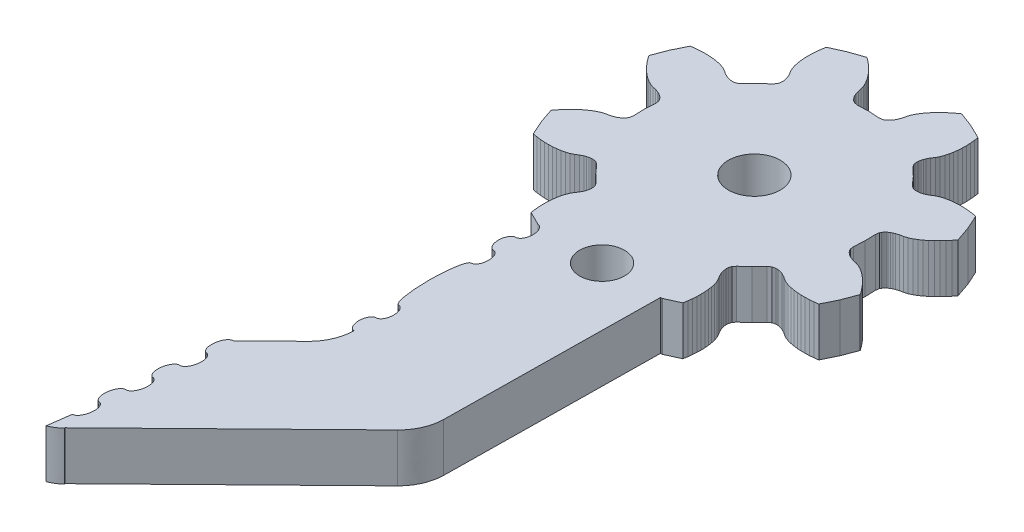
SolidWorks part; units mm, degrees
material "Acrylic (Medium-high impact)"
ref_plane "Front Plane" through (0, 0, 0) normal (0, 0, 1) x (1, 0, 0)
ref_plane "Top Plane" through (0, 0, 0) normal (0, 1, 0) x (1, 0, 0)
ref_plane "Right Plane" through (0, 0, 0) normal (1, 0, 0) x (0, 0, -1)
sketch "Sketch1" plane through (0, 0, 0) normal (0, 1, 0) x (1, 0, 0)
  line L0 (-12.9722, -46.204) -> (-9.9774, -46.2042) construction
  line L1 (-12.7972, -56.1695) -> (-10.1524, -56.2027) construction
  line L104 (-7.6081, -56.2225) -> (-7.5114, -56.2225)
  line L105 (-7.5114, -56.2225) -> (-6.5716, -55.7965)
  line L106 (-6.5716, -55.7965) -> (-6.5251, -55.515)
  line L107 (-6.5251, -55.515) -> (-6.4922, -55.2377)
  line L108 (-6.4922, -55.2377) -> (-6.4726, -54.9654)
  line L109 (-6.4726, -54.9654) -> (-6.467, -54.6985)
  line L110 (-6.467, -54.6985) -> (-6.4753, -54.4376)
  line L111 (-6.4753, -54.4376) -> (-6.4979, -54.184)
  line L112 (-6.4979, -54.184) -> (-6.5358, -53.938)
  line L113 (-6.5358, -53.938) -> (-6.5896, -53.7015)
  line L114 (-6.5896, -53.7015) -> (-6.6624, -53.4766)
  line L115 (-6.6624, -53.4766) -> (-6.7641, -53.2707)
  line L116 (-6.7641, -53.2707) -> (-6.8871, -53.0787)
  line L117 (-6.8871, -53.0787) -> (-6.988, -52.8719)
  line L118 (-6.988, -52.8719) -> (-7.028, -52.7616)
  line L119 (-7.028, -52.7616) -> (-7.0596, -52.6449)
  line L120 (-7.0596, -52.6449) -> (-7.0798, -52.5206)
  line L121 (-7.0798, -52.5206) -> (-7.0845, -52.4542)
  line L122 (-7.0845, -52.4542) -> (-7.0844, -52.3844)
  line L123 (-7.0844, -52.3844) -> (-7.0777, -52.3094)
  line L124 (-7.0777, -52.3094) -> (-7.061, -52.2267)
  line L125 (-7.061, -52.2267) -> (-7.026, -52.1298)
  line L126 (-7.026, -52.1298) -> (-6.8869, -51.9499)
  line L127 (-6.8869, -51.9499) -> (-6.3581, -51.4836)
  line L128 (-6.3581, -51.4836) -> (-5.8762, -50.9687)
  line L129 (-5.8762, -50.9687) -> (-5.6922, -50.835)
  line L130 (-5.6922, -50.835) -> (-5.5944, -50.8032)
  line L131 (-5.5944, -50.8032) -> (-5.5115, -50.7891)
  line L132 (-5.5115, -50.7891) -> (-5.4365, -50.7845)
  line L133 (-5.4365, -50.7845) -> (-5.3668, -50.7865)
  line L134 (-5.3668, -50.7865) -> (-5.3007, -50.7934)
  line L135 (-5.3007, -50.7934) -> (-5.1772, -50.8176)
  line L136 (-5.1772, -50.8176) -> (-5.062, -50.8528)
  line L137 (-5.062, -50.8528) -> (-4.953, -50.8965)
  line L138 (-4.953, -50.8965) -> (-4.7499, -51.0039)
  line L139 (-4.7499, -51.0039) -> (-4.5622, -51.1329)
  line L140 (-4.5622, -51.1329) -> (-4.36, -51.2414)
  line L141 (-4.36, -51.2414) -> (-4.1378, -51.3212)
  line L142 (-4.1378, -51.3212) -> (-3.9037, -51.3827)
  line L143 (-3.9037, -51.3827) -> (-3.6595, -51.4282)
  line L144 (-3.6595, -51.4282) -> (-3.4069, -51.4589)
  line L145 (-3.4069, -51.4589) -> (-3.1472, -51.4754)
  line L146 (-3.1472, -51.4754) -> (-2.8806, -51.4781)
  line L147 (-2.8806, -51.4781) -> (-2.6083, -51.4673)
  line L148 (-2.6083, -51.4673) -> (-2.3306, -51.4429)
  line L149 (-2.3306, -51.4429) -> (-2.0483, -51.4052)
  line L150 (-2.0483, -51.4052) -> (-1.5937, -50.4776)
  line L151 (-1.5937, -50.4776) -> (-1.2299, -49.5105)
  line L152 (-1.2299, -49.5105) -> (-1.3956, -49.2785)
  line L153 (-1.3956, -49.2785) -> (-1.568, -49.0592)
  line L154 (-1.568, -49.0592) -> (-1.7466, -48.8529)
  line L155 (-1.7466, -48.8529) -> (-1.9309, -48.66)
  line L156 (-1.9309, -48.66) -> (-2.1209, -48.4815)
  line L157 (-2.1209, -48.4815) -> (-2.3161, -48.3182)
  line L158 (-2.3161, -48.3182) -> (-2.5163, -48.171)
  line L159 (-2.5163, -48.171) -> (-2.7213, -48.0421)
  line L160 (-2.7213, -48.0421) -> (-2.9315, -47.9345)
  line L161 (-2.9315, -47.9345) -> (-3.1488, -47.861)
  line L162 (-3.1488, -47.861) -> (-3.3712, -47.8122)
  line L163 (-3.3712, -47.8122) -> (-3.5886, -47.7374)
  line L164 (-3.5886, -47.7374) -> (-3.6949, -47.6879)
  line L165 (-3.6949, -47.6879) -> (-3.7993, -47.6278)
  line L166 (-3.7993, -47.6278) -> (-3.9017, -47.5542)
  line L167 (-3.9017, -47.5542) -> (-3.9516, -47.5106)
  line L168 (-3.9516, -47.5106) -> (-4.0009, -47.4611)
  line L169 (-4.0009, -47.4611) -> (-4.0491, -47.403)
  line L170 (-4.0491, -47.403) -> (-4.0955, -47.3328)
  line L171 (-4.0955, -47.3328) -> (-4.1393, -47.2398)
  line L172 (-4.1393, -47.2398) -> (-4.1679, -47.0139)
  line L173 (-4.1679, -47.0139) -> (-4.1232, -46.3095)
  line L174 (-4.1232, -46.3095) -> (-4.1458, -45.6041)
  line L175 (-4.1458, -45.6041) -> (-4.1101, -45.3792)
  line L176 (-4.1101, -45.3792) -> (-4.0634, -45.2876)
  line L177 (-4.0634, -45.2876) -> (-4.0147, -45.2188)
  line L178 (-4.0147, -45.2188) -> (-3.9649, -45.1626)
  line L179 (-3.9649, -45.1626) -> (-3.9141, -45.1145)
  line L180 (-3.9141, -45.1145) -> (-3.8627, -45.0724)
  line L181 (-3.8627, -45.0724) -> (-3.7582, -45.0022)
  line L182 (-3.7582, -45.0022) -> (-3.6519, -44.9454)
  line L183 (-3.6519, -44.9454) -> (-3.544, -44.8991)
  line L184 (-3.544, -44.8991) -> (-3.3245, -44.8313)
  line L185 (-3.3245, -44.8313) -> (-3.1006, -44.7896)
  line L186 (-3.1006, -44.7896) -> (-2.8812, -44.723)
  line L187 (-2.8812, -44.723) -> (-2.6677, -44.6221)
  line L188 (-2.6677, -44.6221) -> (-2.4586, -44.4996)
  line L189 (-2.4586, -44.4996) -> (-2.254, -44.3588)
  line L190 (-2.254, -44.3588) -> (-2.0537, -44.2015)
  line L191 (-2.0537, -44.2015) -> (-1.8585, -44.0292)
  line L192 (-1.8585, -44.0292) -> (-1.6681, -43.8423)
  line L193 (-1.6681, -43.8423) -> (-1.4831, -43.6416)
  line L194 (-1.4831, -43.6416) -> (-1.304, -43.4279)
  line L195 (-1.304, -43.4279) -> (-1.131, -43.2013)
  line L196 (-1.131, -43.2013) -> (-1.4644, -42.2232)
  line L197 (-1.4644, -42.2232) -> (-1.8896, -41.2816)
  line L198 (-1.8896, -41.2816) -> (-2.1705, -41.2351)
  line L199 (-2.1705, -41.2351) -> (-2.4473, -41.202)
  line L200 (-2.4473, -41.202) -> (-2.7192, -41.1825)
  line L201 (-2.7192, -41.1825) -> (-2.9856, -41.1769)
  line L202 (-2.9856, -41.1769) -> (-3.2459, -41.1853)
  line L203 (-3.2459, -41.1853) -> (-3.4992, -41.2079)
  line L204 (-3.4992, -41.2079) -> (-3.7446, -41.2457)
  line L205 (-3.7446, -41.2457) -> (-3.9807, -41.2997)
  line L206 (-3.9807, -41.2997) -> (-4.2052, -41.3725)
  line L207 (-4.2052, -41.3725) -> (-4.4107, -41.4746)
  line L208 (-4.4107, -41.4746) -> (-4.6025, -41.5978)
  line L209 (-4.6025, -41.5978) -> (-4.809, -41.6987)
  line L210 (-4.809, -41.6987) -> (-4.9191, -41.739)
  line L211 (-4.9191, -41.739) -> (-5.0354, -41.7705)
  line L212 (-5.0354, -41.7705) -> (-5.1596, -41.7909)
  line L213 (-5.1596, -41.7909) -> (-5.2257, -41.7956)
  line L214 (-5.2257, -41.7956) -> (-5.2956, -41.7954)
  line L215 (-5.2956, -41.7954) -> (-5.3704, -41.7885)
  line L216 (-5.3704, -41.7885) -> (-5.4528, -41.7718)
  line L217 (-5.4528, -41.7718) -> (-5.5495, -41.737)
  line L218 (-5.5495, -41.737) -> (-5.7293, -41.5975)
  line L219 (-5.7293, -41.5975) -> (-6.1948, -41.0677)
  line L220 (-6.1948, -41.0677) -> (-6.7088, -40.5851)
  line L221 (-6.7088, -40.5851) -> (-6.842, -40.4008)
  line L222 (-6.842, -40.4008) -> (-6.8739, -40.3028)
  line L223 (-6.8739, -40.3028) -> (-6.888, -40.2197)
  line L224 (-6.888, -40.2197) -> (-6.8924, -40.1446)
  line L225 (-6.8924, -40.1446) -> (-6.8906, -40.0745)
  line L226 (-6.8906, -40.0745) -> (-6.8837, -40.0085)
  line L227 (-6.8837, -40.0085) -> (-6.8594, -39.8848)
  line L228 (-6.8594, -39.8848) -> (-6.8243, -39.7694)
  line L229 (-6.8243, -39.7694) -> (-6.7808, -39.6602)
  line L230 (-6.7808, -39.6602) -> (-6.6734, -39.4568)
  line L231 (-6.6734, -39.4568) -> (-6.5447, -39.2687)
  line L232 (-6.5447, -39.2687) -> (-6.4364, -39.066)
  line L233 (-6.4364, -39.066) -> (-6.3567, -38.8435)
  line L234 (-6.3567, -38.8435) -> (-6.2953, -38.6088)
  line L235 (-6.2953, -38.6088) -> (-6.25, -38.3642)
  line L236 (-6.25, -38.3642) -> (-6.2192, -38.1113)
  line L237 (-6.2192, -38.1113) -> (-6.2028, -37.851)
  line L238 (-6.2028, -37.851) -> (-6.2002, -37.5841)
  line L239 (-6.2002, -37.5841) -> (-6.2111, -37.3112)
  line L240 (-6.2111, -37.3112) -> (-6.2353, -37.0331)
  line L241 (-6.2353, -37.0331) -> (-6.2729, -36.7502)
  line L242 (-6.2729, -36.7502) -> (-7.199, -36.2948)
  line L243 (-7.199, -36.2948) -> (-8.1643, -35.9303)
  line L244 (-8.1643, -35.9303) -> (-8.3957, -36.0963)
  line L245 (-8.3957, -36.0963) -> (-8.6147, -36.269)
  line L246 (-8.6147, -36.269) -> (-8.8207, -36.4479)
  line L247 (-8.8207, -36.4479) -> (-9.0131, -36.6326)
  line L248 (-9.0131, -36.6326) -> (-9.1913, -36.823)
  line L249 (-9.1913, -36.823) -> (-9.3545, -37.0183)
  line L250 (-9.3545, -37.0183) -> (-9.5013, -37.2189)
  line L251 (-9.5013, -37.2189) -> (-9.6301, -37.4244)
  line L252 (-9.6301, -37.4244) -> (-9.7373, -37.6349)
  line L253 (-9.7373, -37.6349) -> (-9.8108, -37.8528)
  line L254 (-9.8108, -37.8528) -> (-9.8594, -38.0756)
  line L255 (-9.8594, -38.0756) -> (-9.934, -38.2931)
  line L256 (-9.934, -38.2931) -> (-9.9834, -38.3996)
  line L257 (-9.9834, -38.3996) -> (-10.0435, -38.5044)
  line L258 (-10.0435, -38.5044) -> (-10.1169, -38.6068)
  line L259 (-10.1169, -38.6068) -> (-10.1605, -38.657)
  line L260 (-10.1605, -38.657) -> (-10.21, -38.7062)
  line L261 (-10.21, -38.7062) -> (-10.2677, -38.7545)
  line L262 (-10.2677, -38.7545) -> (-10.3378, -38.8011)
  line L263 (-10.3378, -38.8011) -> (-10.4309, -38.8448)
  line L264 (-10.4309, -38.8448) -> (-10.6564, -38.8737)
  line L265 (-10.6564, -38.8737) -> (-11.3595, -38.8287)
  line L266 (-11.3595, -38.8287) -> (-12.0636, -38.8515)
  line L267 (-12.0636, -38.8515) -> (-12.288, -38.8156)
  line L268 (-12.288, -38.8156) -> (-12.3796, -38.769)
  line L269 (-12.3796, -38.769) -> (-12.4482, -38.7201)
  line L270 (-12.4482, -38.7201) -> (-12.5044, -38.6701)
  line L271 (-12.5044, -38.6701) -> (-12.5523, -38.6193)
  line L272 (-12.5523, -38.6193) -> (-12.5942, -38.5678)
  line L273 (-12.5942, -38.5678) -> (-12.6645, -38.4631)
  line L274 (-12.6645, -38.4631) -> (-12.7211, -38.3566)
  line L275 (-12.7211, -38.3566) -> (-12.7673, -38.2486)
  line L276 (-12.7673, -38.2486) -> (-12.835, -38.0288)
  line L277 (-12.835, -38.0288) -> (-12.8765, -37.8045)
  line L278 (-12.8765, -37.8045) -> (-12.9431, -37.5846)
  line L279 (-12.9431, -37.5846) -> (-13.0439, -37.3707)
  line L280 (-13.0439, -37.3707) -> (-13.1661, -37.1613)
  line L281 (-13.1661, -37.1613) -> (-13.3065, -36.9563)
  line L282 (-13.3065, -36.9563) -> (-13.4634, -36.7557)
  line L283 (-13.4634, -36.7557) -> (-13.6357, -36.5599)
  line L284 (-13.6357, -36.5599) -> (-13.8221, -36.3692)
  line L285 (-13.8221, -36.3692) -> (-14.0224, -36.184)
  line L286 (-14.0224, -36.184) -> (-14.2359, -36.0044)
  line L287 (-14.2359, -36.0044) -> (-14.4621, -35.8312)
  line L288 (-14.4621, -35.8312) -> (-15.4384, -36.1651)
  line L289 (-15.4384, -36.1651) -> (-16.3783, -36.5911)
  line L290 (-16.3783, -36.5911) -> (-16.4247, -36.8727)
  line L291 (-16.4247, -36.8727) -> (-16.4578, -37.1499)
  line L292 (-16.4578, -37.1499) -> (-16.477, -37.4222)
  line L293 (-16.477, -37.4222) -> (-16.4826, -37.6893)
  line L294 (-16.4826, -37.6893) -> (-16.4745, -37.95)
  line L295 (-16.4745, -37.95) -> (-16.4517, -38.2038)
  line L296 (-16.4517, -38.2038) -> (-16.4141, -38.4497)
  line L297 (-16.4141, -38.4497) -> (-16.36, -38.6861)
  line L298 (-16.36, -38.6861) -> (-16.2874, -38.911)
  line L299 (-16.2874, -38.911) -> (-16.1854, -39.117)
  line L300 (-16.1854, -39.117) -> (-16.0626, -39.3089)
  line L301 (-16.0626, -39.3089) -> (-15.9617, -39.5157)
  line L302 (-15.9617, -39.5157) -> (-15.9218, -39.6261)
  line L303 (-15.9218, -39.6261) -> (-15.8901, -39.7427)
  line L304 (-15.8901, -39.7427) -> (-15.8699, -39.8672)
  line L305 (-15.8699, -39.8672) -> (-15.8652, -39.9334)
  line L306 (-15.8652, -39.9334) -> (-15.8654, -40.0032)
  line L307 (-15.8654, -40.0032) -> (-15.8721, -40.0784)
  line L308 (-15.8721, -40.0784) -> (-15.8888, -40.1609)
  line L309 (-15.8888, -40.1609) -> (-15.9237, -40.2578)
  line L310 (-15.9237, -40.2578) -> (-16.0628, -40.4378)
  line L311 (-16.0628, -40.4378) -> (-16.5916, -40.9042)
  line L312 (-16.5916, -40.9042) -> (-17.0735, -41.419)
  line L313 (-17.0735, -41.419) -> (-17.2575, -41.5527)
  line L314 (-17.2575, -41.5527) -> (-17.3552, -41.5844)
  line L315 (-17.3552, -41.5844) -> (-17.4381, -41.5985)
  line L316 (-17.4381, -41.5985) -> (-17.5133, -41.6031)
  line L317 (-17.5133, -41.6031) -> (-17.583, -41.6011)
  line L318 (-17.583, -41.6011) -> (-17.6491, -41.5944)
  line L319 (-17.6491, -41.5944) -> (-17.7726, -41.5701)
  line L320 (-17.7726, -41.5701) -> (-17.8878, -41.5349)
  line L321 (-17.8878, -41.5349) -> (-17.9966, -41.4911)
  line L322 (-17.9966, -41.4911) -> (-18.1998, -41.3838)
  line L323 (-18.1998, -41.3838) -> (-18.3875, -41.2547)
  line L324 (-18.3875, -41.2547) -> (-18.5899, -41.1462)
  line L325 (-18.5899, -41.1462) -> (-18.812, -41.0664)
  line L326 (-18.812, -41.0664) -> (-19.0461, -41.0049)
  line L327 (-19.0461, -41.0049) -> (-19.2902, -40.9594)
  line L328 (-19.2902, -40.9594) -> (-19.5427, -40.9287)
  line L329 (-19.5427, -40.9287) -> (-19.8027, -40.9122)
  line L330 (-19.8027, -40.9122) -> (-20.0692, -40.9095)
  line L331 (-20.0692, -40.9095) -> (-20.3415, -40.9204)
  line L332 (-20.3415, -40.9204) -> (-20.6192, -40.9447)
  line L333 (-20.6192, -40.9447) -> (-20.9015, -40.9824)
  line L334 (-20.9015, -40.9824) -> (-21.3561, -41.9101)
  line L335 (-21.3561, -41.9101) -> (-21.7199, -42.8771)
  line L336 (-21.7199, -42.8771) -> (-21.554, -43.1091)
  line L337 (-21.554, -43.1091) -> (-21.3818, -43.3285)
  line L338 (-21.3818, -43.3285) -> (-21.2032, -43.5347)
  line L339 (-21.2032, -43.5347) -> (-21.0187, -43.7277)
  line L340 (-21.0187, -43.7277) -> (-20.8289, -43.9062)
  line L341 (-20.8289, -43.9062) -> (-20.6337, -44.0696)
  line L342 (-20.6337, -44.0696) -> (-20.4335, -44.2168)
  line L343 (-20.4335, -44.2168) -> (-20.2284, -44.3456)
  line L344 (-20.2284, -44.3456) -> (-20.0183, -44.4531)
  line L345 (-20.0183, -44.4531) -> (-19.801, -44.5266)
  line L346 (-19.801, -44.5266) -> (-19.5786, -44.5755)
  line L347 (-19.5786, -44.5755) -> (-19.3612, -44.6502)
  line L348 (-19.3612, -44.6502) -> (-19.255, -44.6998)
  line L349 (-19.255, -44.6998) -> (-19.1504, -44.76)
  line L350 (-19.1504, -44.76) -> (-19.0481, -44.8335)
  line L351 (-19.0481, -44.8335) -> (-18.9981, -44.877)
  line L352 (-18.9981, -44.877) -> (-18.9489, -44.9267)
  line L353 (-18.9489, -44.9267) -> (-18.9009, -44.9846)
  line L354 (-18.9009, -44.9846) -> (-18.8543, -45.0548)
  line L355 (-18.8543, -45.0548) -> (-18.8105, -45.1479)
  line L356 (-18.8105, -45.1479) -> (-18.7817, -45.3737)
  line L357 (-18.7817, -45.3737) -> (-18.8266, -46.0782)
  line L358 (-18.8266, -46.0782) -> (-18.804, -46.7836)
  line L359 (-18.804, -46.7836) -> (-18.8397, -47.0085)
  line L360 (-18.8397, -47.0085) -> (-18.8864, -47.1002)
  line L361 (-18.8864, -47.1002) -> (-18.9351, -47.1688)
  line L362 (-18.9351, -47.1688) -> (-18.9849, -47.2252)
  line L363 (-18.9849, -47.2252) -> (-19.0356, -47.2731)
  line L364 (-19.0356, -47.2731) -> (-19.0871, -47.3152)
  line L365 (-19.0871, -47.3152) -> (-19.1915, -47.3855)
  line L366 (-19.1915, -47.3855) -> (-19.2978, -47.4422)
  line L367 (-19.2978, -47.4422) -> (-19.4058, -47.4885)
  line L368 (-19.4058, -47.4885) -> (-19.6252, -47.5565)
  line L369 (-19.6252, -47.5565) -> (-19.8489, -47.5981)
  line L370 (-19.8489, -47.5981) -> (-20.0686, -47.6648)
  line L371 (-20.0686, -47.6648) -> (-20.282, -47.7656)
  line L372 (-20.282, -47.7656) -> (-20.4911, -47.8882)
  line L373 (-20.4911, -47.8882) -> (-20.6958, -48.0288)
  line L374 (-20.6958, -48.0288) -> (-20.8959, -48.1861)
  line L375 (-20.8959, -48.1861) -> (-21.0915, -48.3584)
  line L376 (-21.0915, -48.3584) -> (-21.2818, -48.5453)
  line L377 (-21.2818, -48.5453) -> (-21.4667, -48.746)
  line L378 (-21.4667, -48.746) -> (-21.6459, -48.9599)
  line L379 (-21.6459, -48.9599) -> (-21.8188, -49.1865)
  line L380 (-21.8188, -49.1865) -> (-21.4856, -50.1646)
  line L381 (-21.4856, -50.1646) -> (-21.0601, -51.106)
  line L382 (-21.0601, -51.106) -> (-20.7793, -51.1527)
  line L383 (-20.7793, -51.1527) -> (-20.5024, -51.1856)
  line L384 (-20.5024, -51.1856) -> (-20.2305, -51.2051)
  line L385 (-20.2305, -51.2051) -> (-19.9641, -51.2107)
  line L386 (-19.9641, -51.2107) -> (-19.7039, -51.2024)
  line L387 (-19.7039, -51.2024) -> (-19.4505, -51.1797)
  line L388 (-19.4505, -51.1797) -> (-19.2051, -51.1419)
  line L389 (-19.2051, -51.1419) -> (-18.9691, -51.0879)
  line L390 (-18.9691, -51.0879) -> (-18.7446, -51.0151)
  line L391 (-18.7446, -51.0151) -> (-18.5388, -50.913)
  line L392 (-18.5388, -50.913) -> (-18.3474, -50.79)
  line L393 (-18.3474, -50.79) -> (-18.141, -50.6889)
  line L394 (-18.141, -50.6889) -> (-18.0307, -50.6486)
  line L395 (-18.0307, -50.6486) -> (-17.9144, -50.6171)
  line L396 (-17.9144, -50.6171) -> (-17.7902, -50.5967)
  line L397 (-17.7902, -50.5967) -> (-17.7239, -50.592)
  line L398 (-17.7239, -50.592) -> (-17.6542, -50.5924)
  line L399 (-17.6542, -50.5924) -> (-17.5794, -50.5991)
  line L400 (-17.5794, -50.5991) -> (-17.4968, -50.6158)
  line L401 (-17.4968, -50.6158) -> (-17.4003, -50.6506)
  line L402 (-17.4003, -50.6506) -> (-17.2204, -50.7902)
  line L403 (-17.2204, -50.7902) -> (-16.755, -51.3199)
  line L404 (-16.755, -51.3199) -> (-16.241, -51.8027)
  line L405 (-16.241, -51.8027) -> (-16.1076, -51.987)
  line L406 (-16.1076, -51.987) -> (-16.0759, -52.0848)
  line L407 (-16.0759, -52.0848) -> (-16.0617, -52.1679)
  line L408 (-16.0617, -52.1679) -> (-16.0574, -52.2431)
  line L409 (-16.0574, -52.2431) -> (-16.0592, -52.3131)
  line L410 (-16.0592, -52.3131) -> (-16.0661, -52.3791)
  line L411 (-16.0661, -52.3791) -> (-16.0904, -52.5029)
  line L412 (-16.0904, -52.5029) -> (-16.1255, -52.6184)
  line L413 (-16.1255, -52.6184) -> (-16.1689, -52.7275)
  line L414 (-16.1689, -52.7275) -> (-16.2761, -52.9309)
  line L415 (-16.2761, -52.9309) -> (-16.4051, -53.119)
  line L416 (-16.4051, -53.119) -> (-16.5134, -53.3217)
  line L417 (-16.5134, -53.3217) -> (-16.5931, -53.5441)
  line L418 (-16.5931, -53.5441) -> (-16.6545, -53.7789)
  line L419 (-16.6545, -53.7789) -> (-16.6998, -54.0234)
  line L420 (-16.6998, -54.0234) -> (-16.7304, -54.2764)
  line L421 (-16.7304, -54.2764) -> (-16.7469, -54.5367)
  line L422 (-16.7469, -54.5367) -> (-16.7496, -54.8038)
  line L423 (-16.7496, -54.8038) -> (-16.7389, -55.0764)
  line L424 (-16.7389, -55.0764) -> (-16.7144, -55.3548)
  line L425 (-16.7144, -55.3548) -> (-16.6769, -55.6374)
  line L426 (-16.6769, -55.6374) -> (-15.7508, -56.093)
  line L427 (-15.7508, -56.093) -> (-15.764, -56.093)
  line L428 (-16.6675, -70.2592) -> (-19.1419, -72.6771)
  line L429 (-20.2503, -82.1129) -> (-20.4524, -83.6175)
  line L430 (-20.4524, -83.6175) -> (-20.4797, -83.6172)
  line L431 (-19.7077, -83.1676) -> (-19.7215, -83.1215)
  line L432 (-19.7215, -83.1215) -> (-8.7072, -72.3589)
  line L433 (-8.7072, -72.3589) -> (-8.7057, -72.3554)
  line L434 (-7.7901, -70.2503) -> (-7.6081, -56.2225)
  circle A0 centre (-11.4748, -46.2041) radius 1.7
  circle A1 centre (-11.4748, -56.1861) radius 1.4681
  spline S9 degree 3 poles (-15.764, -56.093) (-15.5362, -56.0961) (-15.3516, -56.4254) (-15.3516, -56.8283) knots 324 324 324 324 325 325 325 325
  spline S10 degree 3 poles (-15.3516, -56.8283) (-15.3516, -57.2314) (-15.5362, -57.5553) (-15.764, -57.5522) knots 325 325 325 325 326 326 326 326
  spline S11 degree 3 poles (-15.764, -57.5522) (-15.9917, -57.5492) (-16.1762, -57.8731) (-16.1762, -58.2761) knots 326 326 326 326 327 327 327 327
  spline S12 degree 3 poles (-16.1762, -58.2761) (-16.1762, -58.6791) (-15.9917, -59.0084) (-15.764, -59.0117) knots 327 327 327 327 328 328 328 328
  spline S13 degree 3 poles (-15.764, -59.0117) (-15.5362, -59.0149) (-15.3516, -59.344) (-15.3516, -59.747) knots 328 328 328 328 329 329 329 329
  spline S14 degree 3 poles (-15.3516, -59.747) (-15.3516, -60.1499) (-15.5362, -60.4742) (-15.764, -60.4711) knots 329 329 329 329 330 330 330 330
  spline S15 degree 3 poles (-15.764, -60.4711) (-15.9919, -60.4607) (-16.1764, -61.5178) (-16.1764, -62.8318) knots 330 330 330 330 331 331 331 331
  spline S16 degree 3 poles (-16.1764, -62.8318) (-16.1764, -64.1461) (-15.9919, -65.2198) (-15.764, -65.2303) knots 331 331 331 331 332 332 332 332
  spline S17 degree 3 poles (-15.764, -65.2303) (-15.5364, -65.2336) (-15.3518, -65.5627) (-15.3518, -65.9659) knots 332 332 332 332 333 333 333 333
  spline S18 degree 3 poles (-15.3518, -65.9659) (-15.3518, -66.3686) (-15.5364, -66.6928) (-15.764, -66.6896) knots 333 333 333 333 334 334 334 334
  spline S19 degree 3 poles (-15.764, -66.6896) (-15.9919, -66.6865) (-16.1764, -67.0105) (-16.1764, -67.4135) knots 334 334 334 334 335 335 335 335
  spline S20 degree 3 poles (-16.1764, -67.4135) (-16.1764, -67.8164) (-15.9919, -68.1457) (-15.764, -68.1488) knots 335 335 335 335 336 336 336 336
  spline S21 degree 3 poles (-15.764, -68.1488) (-15.774, -68.9446) (-16.099, -69.7037) (-16.6675, -70.2592) knots 336 336 336 336 337 337 337 337
  spline S22 degree 3 poles (-19.1419, -72.6771) (-19.3685, -72.6539) (-19.5934, -72.9872) (-19.6445, -73.4214) knots 338 338 338 338 339 339 339 339
  spline S23 degree 3 poles (-19.6445, -73.4214) (-19.6955, -73.8557) (-19.5532, -74.2265) (-19.3266, -74.2498) knots 339 339 339 339 340 340 340 340
  spline S24 degree 3 poles (-19.3266, -74.2498) (-19.1001, -74.273) (-18.9579, -74.6438) (-19.0088, -75.078) knots 340 340 340 340 341 341 341 341
  spline S25 degree 3 poles (-19.0088, -75.078) (-19.0599, -75.5123) (-19.285, -75.8456) (-19.5113, -75.8224) knots 341 341 341 341 342 342 342 342
  spline S26 degree 3 poles (-19.5113, -75.8224) (-19.738, -75.7992) (-19.9628, -76.1325) (-20.014, -76.5666) knots 342 342 342 342 343 343 343 343
  spline S27 degree 3 poles (-20.014, -76.5666) (-20.065, -77.0009) (-19.9227, -77.3718) (-19.6961, -77.395) knots 343 343 343 343 344 344 344 344
  spline S28 degree 3 poles (-19.6961, -77.395) (-19.4696, -77.4182) (-19.3274, -77.7891) (-19.3783, -78.2232) knots 344 344 344 344 345 345 345 345
  spline S29 degree 3 poles (-19.3783, -78.2232) (-19.4293, -78.6576) (-19.6545, -78.9909) (-19.8808, -78.9677) knots 345 345 345 345 346 346 346 346
  spline S30 degree 3 poles (-19.8808, -78.9677) (-20.1074, -78.9444) (-20.3323, -79.2777) (-20.3834, -79.7121) knots 346 346 346 346 347 347 347 347
  spline S31 degree 3 poles (-20.3834, -79.7121) (-20.4345, -80.1462) (-20.2921, -80.5171) (-20.0655, -80.5403) knots 347 347 347 347 348 348 348 348
  spline S32 degree 3 poles (-20.0655, -80.5403) (-19.839, -80.5635) (-19.6966, -80.9344) (-19.7477, -81.3687) knots 348 348 348 348 349 349 349 349
  spline S33 degree 3 poles (-19.7477, -81.3687) (-19.7988, -81.8029) (-20.0237, -82.1361) (-20.2503, -82.1129) knots 349 349 349 349 350 350 350 350
  spline S34 degree 3 poles (-20.4797, -83.6172) (-20.4805, -83.6843) (-19.9458, -83.4002) (-19.7077, -83.1676) knots 352 352 352 352 353 353 353 353
  spline S35 degree 3 poles (-8.7057, -72.3554) (-8.1339, -71.8032) (-7.8046, -71.0459) (-7.7901, -70.2503) knots 356 356 356 356 357 357 357 357
  point P4 (0, 0)
  dimension "D1" = 3.4
  dimension "D2" = 9.982
extrude "Boss-Extrude1" add sketch "Sketch1" along normal blind 3.175
